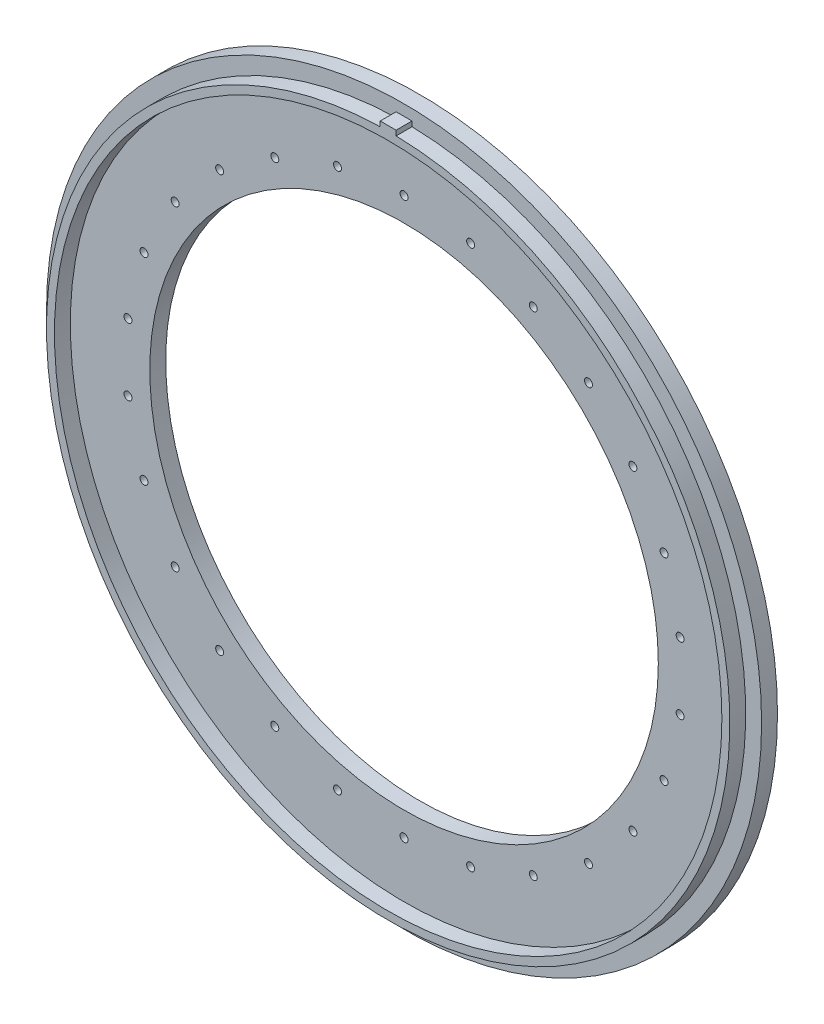
SolidWorks part; units mm, degrees
ref_plane "Front Plane" through (0, 0, 0) normal (0, 0, 1) x (1, 0, 0)
ref_plane "Top Plane" through (0, 0, 0) normal (0, 1, 0) x (1, 0, 0)
ref_plane "Right Plane" through (0, 0, 0) normal (1, 0, 0) x (0, 0, -1)
sketch "Sketch1" plane through (0, 0, 0) normal (0, 0, 1) x (1, 0, 0)
  circle A0 centre (0, 0) radius 45
  dimension "D1" = 90
extrude "Boss-Extrude1" add sketch "Sketch1" along normal blind 2
sketch "Sketch2" plane through (0, 0, 2) normal (0, 0, 1) x (1, 0, 0)
  line L0 (0, 0) -> (0, 56.449) construction
  line L2 (-1, 43.6175) -> (1, 43.6175)
  line L3 (-1, 43.6175) -> (-1, 42.9884)
  line L4 (1, 43.6175) -> (1, 42.9884)
  arc A0 (-1, 42.9884) -> (1, 42.9884) centre (0, 0) ccw
  circle A2 centre (0, 0) radius 45 construction
  circle A3 centre (0, 0) radius 42
  dimension "D1" = 2
  dimension "D2" = 1
  dimension "D3" = 2
extrude "Boss-Extrude2" add sketch "Sketch2" along normal blind 2
sketch "Sketch3" plane through (0, 0, 2) normal (0, 0, 1) x (1, 0, 0)
  line L0 (0, 0) -> (0, 55.873) construction
  circle A0 centre (0, 35) radius 0.5
  circle A1 centre (8.376, 33.983) radius 0.5
  circle A2 centre (16.2653, 30.991) radius 0.5
  circle A3 centre (23.2093, 26.1979) radius 0.5
  circle A4 centre (28.8044, 19.8823) radius 0.5
  circle A5 centre (32.7256, 12.4112) radius 0.5
  circle A6 centre (34.7448, 4.2188) radius 0.5
  circle A7 centre (34.7448, -4.2188) radius 0.5
  circle A8 centre (32.7256, -12.4112) radius 0.5
  circle A9 centre (28.8044, -19.8823) radius 0.5
  circle A10 centre (23.2093, -26.1979) radius 0.5
  circle A11 centre (16.2653, -30.991) radius 0.5
  circle A12 centre (8.376, -33.983) radius 0.5
  circle A13 centre (0, -35) radius 0.5
  circle A14 centre (-8.376, -33.983) radius 0.5
  circle A15 centre (-16.2653, -30.991) radius 0.5
  circle A16 centre (-23.2093, -26.1979) radius 0.5
  circle A17 centre (-28.8044, -19.8823) radius 0.5
  circle A18 centre (-32.7256, -12.4112) radius 0.5
  circle A19 centre (-34.7448, -4.2188) radius 0.5
  circle A20 centre (-34.7448, 4.2188) radius 0.5
  circle A21 centre (-32.7256, 12.4112) radius 0.5
  circle A22 centre (-28.8044, 19.8823) radius 0.5
  circle A23 centre (-23.2093, 26.1979) radius 0.5
  circle A24 centre (-16.2653, 30.991) radius 0.5
  circle A25 centre (-8.376, 33.983) radius 0.5
  circle A26 centre (0, 0) radius 32
  point P57 (0, 0)
  dimension "D1" = 35
  dimension "D3" = 1
  dimension "D4" = 64
  dimension "D2" = 26
extrude "Cut-Extrude1" cut sketch "Sketch3" against normal through all
